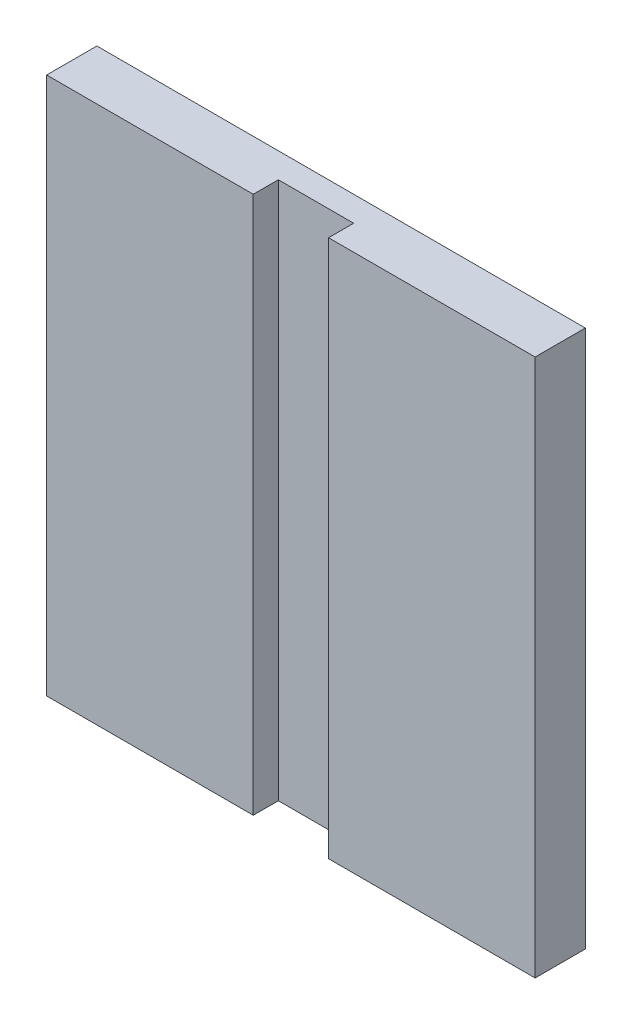
SolidWorks part; units mm, degrees
ref_plane "Front Plane" through (0, 0, 0) normal (0, 0, 1) x (1, 0, 0)
ref_plane "Top Plane" through (0, 0, 0) normal (0, 1, 0) x (1, 0, 0)
ref_plane "Right Plane" through (0, 0, 0) normal (1, 0, 0) x (0, 0, -1)
sketch "Sketch1" plane through (0, 0, 0) normal (0, 0, 1) x (1, 0, 0)
  line L1 (-50.2434, 46.6804) -> (47.0542, 46.6804)
  line L2 (-50.2434, 46.6804) -> (-50.2434, -60.4476)
  line L3 (-50.2434, -60.4476) -> (47.0542, -60.4476)
  line L4 (47.0542, 46.6804) -> (47.0542, -60.4476)
extrude "Boss-Extrude2" add sketch "Sketch1" along normal blind 10 contours L2 L1 L4 L3
sketch "Sketch2" plane through (0, 0, 10) normal (0, 0, 1) x (1, 0, 0)
  line L0 (-50.2434, 46.6804) -> (47.0542, 46.6804) construction
  line L1 (-9.0946, 46.6804) -> (5.9054, 46.6804)
  line L2 (-9.0946, 46.6804) -> (-9.0946, -60.4476)
  line L3 (-9.0946, -60.4476) -> (5.9054, -60.4476)
  line L4 (5.9054, 46.6804) -> (5.9054, -60.4476)
  line L5 (-50.2434, -60.4476) -> (47.0542, -60.4476) construction
  point P8 (-1.5946, 46.6804)
  point P9 (-1.5946, 46.6804)
extrude "Cut-Extrude1" cut sketch "Sketch2" against normal blind 5
